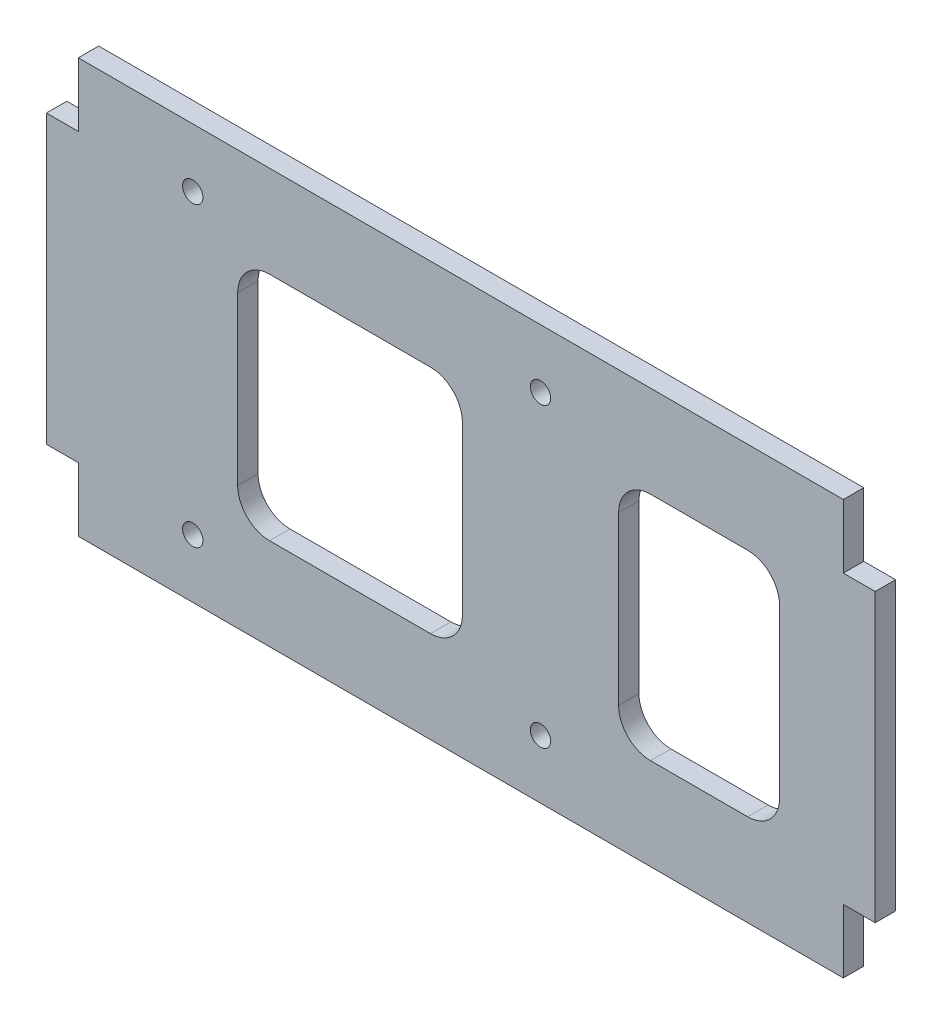
SolidWorks part; units mm, degrees
ref_plane "Front Plane" through (0, 0, 0) normal (0, 0, 1) x (1, 0, 0)
ref_plane "Top Plane" through (0, 0, 0) normal (0, 1, 0) x (1, 0, 0)
ref_plane "Right Plane" through (0, 0, 0) normal (1, 0, 0) x (0, 0, -1)
sketch "Sketch1" plane through (0, 0, 0) normal (0, 0, 1) x (1, 0, 0)
  line L0 (75.8825, -41.275) -> (-76.5175, -41.275)
  line L1 (75.8825, 41.275) -> (-76.5175, 41.275)
  line L2 (56.8325, 22.987) -> (37.465, 22.987)
  line L3 (-6.35, 22.987) -> (-38.4175, 22.987)
  line L4 (-82.8675, 28.575) -> (-82.8675, -28.575)
  line L5 (-76.5175, 41.275) -> (-76.5175, 28.575)
  line L6 (-76.5175, -28.575) -> (-76.5175, -41.275)
  line L7 (-82.8675, 28.575) -> (-76.5175, 28.575)
  line L8 (-82.8675, -28.575) -> (-76.5175, -28.575)
  line L9 (82.2325, 28.575) -> (82.2325, -28.575)
  line L10 (75.8825, 41.275) -> (75.8825, 28.575)
  line L11 (75.8825, -28.575) -> (75.8825, -41.275)
  line L12 (82.2325, 28.575) -> (75.8825, 28.575)
  line L13 (82.2325, -28.575) -> (75.8825, -28.575)
  line L14 (56.8325, -22.987) -> (37.465, -22.987)
  line L15 (-6.35, -22.987) -> (-38.4175, -22.987)
  line L16 (-44.7675, 16.637) -> (-44.7675, -16.637)
  line L17 (0, -16.637) -> (0, 16.637)
  line L18 (31.115, 16.637) -> (31.115, -16.637)
  line L19 (63.1825, 16.637) -> (63.1825, -16.637)
  arc A0 (37.465, 22.987) -> (31.115, 16.637) centre (37.465, 16.637) ccw
  arc A1 (63.1825, 16.637) -> (56.8325, 22.987) centre (56.8325, 16.637) ccw
  arc A2 (0, 16.637) -> (-6.35, 22.987) centre (-6.35, 16.637) ccw
  arc A3 (-38.4175, 22.987) -> (-44.7675, 16.637) centre (-38.4175, 16.637) ccw
  arc A4 (31.115, -16.637) -> (37.465, -22.987) centre (37.465, -16.637) ccw
  arc A5 (56.8325, -22.987) -> (63.1825, -16.637) centre (56.8325, -16.637) ccw
  arc A6 (-6.35, -22.987) -> (0, -16.637) centre (-6.35, -16.637) ccw
  arc A7 (-44.7675, -16.637) -> (-38.4175, -22.987) centre (-38.4175, -16.637) ccw
  circle A8 centre (-53.7098, 29.591) radius 2.032
  circle A9 centre (15.5575, 29.591) radius 2.032
  circle A10 centre (-53.7098, -29.591) radius 2.032
  circle A11 centre (15.5575, -29.591) radius 2.032
extrude "Boss-Extrude1" add sketch "Sketch1" along normal blind 4.064
